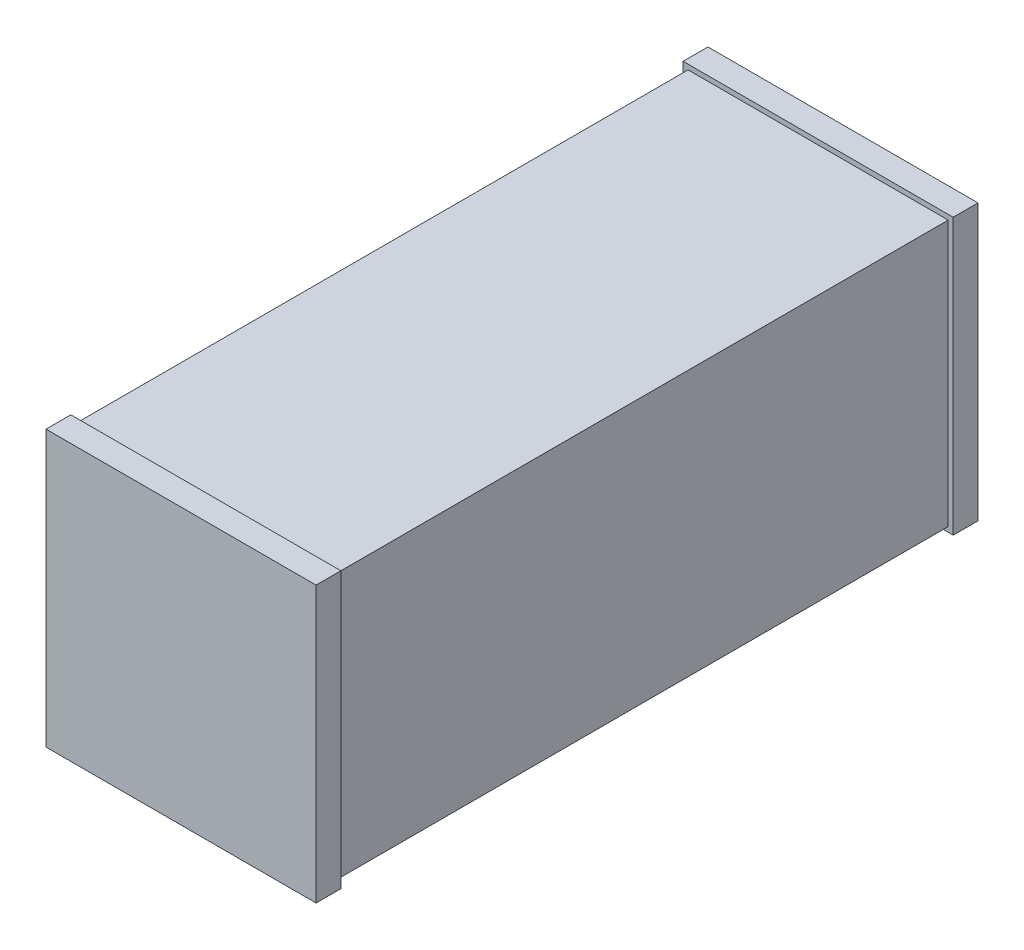
SolidWorks part; units mm, degrees
ref_plane "Front Plane" through (0, 0, 0) normal (0, 0, 1) x (1, 0, 0)
ref_plane "Top Plane" through (0, 0, 0) normal (0, 1, 0) x (1, 0, 0)
ref_plane "Right Plane" through (0, 0, 0) normal (1, 0, 0) x (0, 0, -1)
other "Center of Mass"
sketch "Sketch1" plane through (0, 0, 0) normal (0, 0, 1) x (1, 0, 0)
  line L1 (0, 0) -> (103.632, 0)
  line L2 (0, 0) -> (0, -105.664)
  line L3 (0, -105.664) -> (103.632, -105.664)
  line L4 (103.632, 0) -> (103.632, -105.664)
  dimension "D1" = 103.632
  dimension "D2" = 105.664
extrude "Boss-Extrude1" add sketch "Sketch1" against normal blind 9.525
sketch "Sketch2" plane through (0, 0, -9.525) normal (0, 0, -1) x (-1, 0, 0)
  line L0 (-103.632, 0) -> (0, 0) construction
  line L1 (-101.727, -1.905) -> (-1.905, -1.905)
  line L2 (-101.727, -1.905) -> (-101.727, -103.759)
  line L3 (-101.727, -103.759) -> (-1.905, -103.759)
  line L4 (-1.905, -1.905) -> (-1.905, -103.759)
  line L5 (-103.632, -105.664) -> (-103.632, 0) construction
  line L6 (0, 0) -> (0, -105.664) construction
  line L7 (0, -105.664) -> (-103.632, -105.664) construction
  dimension "D1" = 1.905
  dimension "D2" = 1.905
  dimension "D3" = 1.905
  dimension "D4" = 1.905
extrude "Boss-Extrude2" add sketch "Sketch2" along normal blind 234.95
sketch "Sketch4" plane through (0, 0, -244.475) normal (0, 0, -1) x (-1, 0, 0)
  line L8 (0, 0) -> (-103.632, 0)
  line L9 (-103.632, 0) -> (-103.632, -105.664)
  line L10 (-103.632, -105.664) -> (0, -105.664)
  line L11 (0, -105.664) -> (0, 0)
  line L12 (0, 0) -> (-103.632, 0)
  line L13 (-103.632, 0) -> (-103.632, -105.664)
  line L14 (-103.632, -105.664) -> (0, -105.664)
  line L15 (0, -105.664) -> (0, 0)
  dimension "D1" = 0
extrude "Boss-Extrude5" add sketch "Sketch4" along normal blind 9.525
sketch "Sketch5" plane through (0, -103.759, 0) normal (0, -1, 0) x (1, 0, 0)
  line L0 (101.727, -9.525) -> (1.905, -9.525) construction
  line L2 (15.3035, -19.05) -> (1.905, -19.05) construction
  line L3 (1.905, -244.475) -> (1.905, -9.525) construction
  line L4 (88.3285, -19.05) -> (101.727, -19.05) construction
  line L5 (101.727, -244.475) -> (101.727, -9.525) construction
  line L6 (15.3035, -234.95) -> (1.905, -234.95) construction
  line L7 (88.3285, -234.95) -> (101.727, -234.95) construction
  point P0 (15.3035, -19.05)
  point P1 (88.3285, -19.05)
  point P2 (15.3035, -234.95)
  point P3 (88.3285, -234.95)
  dimension "D1" = 73.025
  dimension "D2" = 215.9
  dimension "D3" = 9.525
hole_wizard "Tap Drill for #6-32 Tap1" positions "Sketch6" profile "Sketch7" hole size "#6-32" standard "ANSI Inch"
sketch "Sketch6" plane through (0, -103.759, 0) normal (0, -1, 0) x (-1, 0, 0)
  point P0 (-88.3285, 234.95)
  point P3 (-15.3035, 234.95)
  point P6 (-88.3285, 19.05)
  point P9 (-15.3035, 19.05)
sketch "Sketch7" plane through (88.3285, -103.759, -234.95) normal (1, 0, 0) x (0, 0, -1)
  line L0 (0, 0) -> (0, 4.7827)
  line L1 (0, 4.7827) -> (1.3525, 3.97)
  line L2 (1.3525, 3.97) -> (1.3525, 0)
  line L5 (1.3525, 0) -> (0, 0)
  line L10 (0, 4.7827) -> (-1.3526, 3.97) construction
  line L11 (0, -6.35) -> (0, 107.95) construction
  dimension "Hole Dia." = 2.7051
  dimension "Hole Depth" = 3.97
  dimension "Drill Angle" = 118
